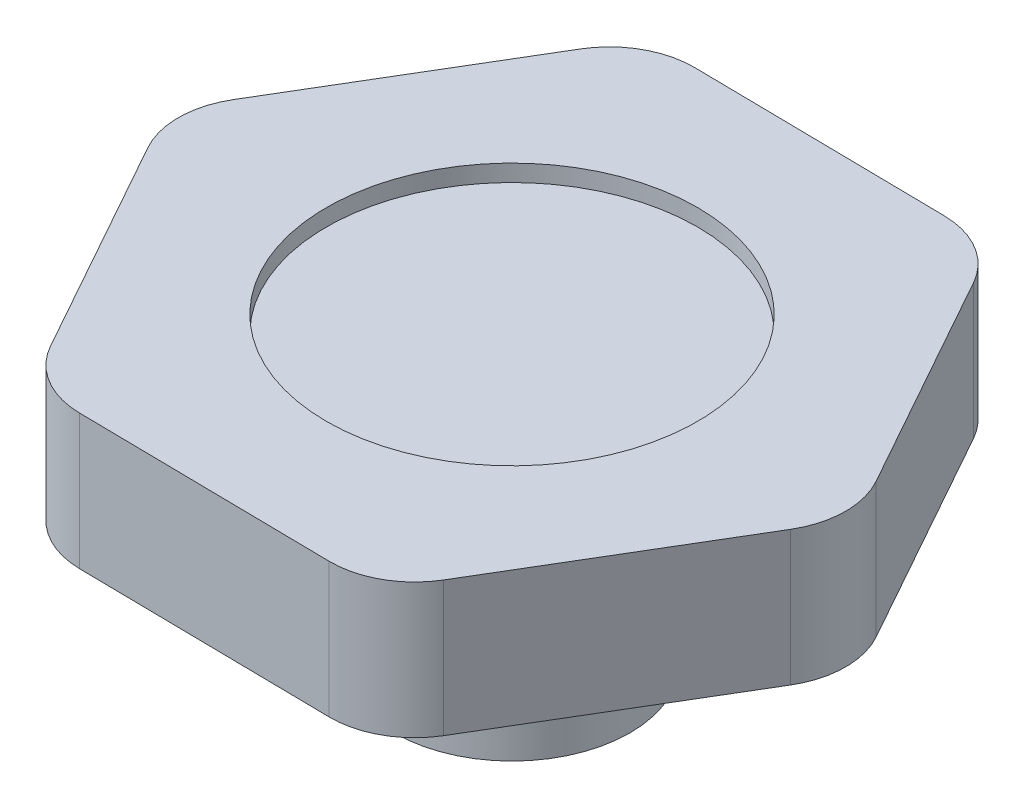
SolidWorks part; units mm, degrees
ref_plane "Front Plane" through (0, 0, 0) normal (0, 0, 1) x (1, 0, 0)
ref_plane "Top Plane" through (0, 0, 0) normal (0, 1, 0) x (1, 0, 0)
ref_plane "Right Plane" through (0, 0, 0) normal (1, 0, 0) x (0, 0, -1)
sketch "Sketch1" plane through (0, 0, 0) normal (0, 1, 0) x (1, 0, 0)
  circle A1 centre (0, 0) radius 7
  dimension "D1" = 14
extrude "Boss-Extrude1" add sketch "Sketch1" along normal blind 10
sketch "Sketch2" plane through (0, 0, 0) normal (0, -1, 0) x (1, 0, 0)
  line L1 (4.7639, -2.7182) -> (4.736, 2.7665)
  line L2 (4.736, 2.7665) -> (-0.0279, 5.4848)
  line L3 (-0.0279, 5.4848) -> (-4.7639, 2.7182)
  line L4 (-4.7639, 2.7182) -> (-4.736, -2.7665)
  line L5 (-4.736, -2.7665) -> (0.0279, -5.4848)
  line L6 (0.0279, -5.4848) -> (4.7639, -2.7182)
  circle A0 centre (0, 0) radius 4.75 construction
extrude "Cut-Extrude1" cut sketch "Sketch2" against normal blind 5
sketch "Sketch3" plane through (0, 10, 0) normal (0, 1, 0) x (1, 0, 0)
  line L1 (20.7825, -0.295) -> (10.6467, 17.8507)
  line L2 (10.6467, 17.8507) -> (-10.1358, 18.1457)
  line L3 (-10.1358, 18.1457) -> (-20.7825, 0.295)
  line L4 (-20.7825, 0.295) -> (-10.6467, -17.8507)
  line L5 (-10.6467, -17.8507) -> (10.1358, -18.1457)
  line L6 (10.1358, -18.1457) -> (20.7825, -0.295)
  circle A0 centre (0, 0) radius 18 construction
extrude "Boss-Extrude2" add sketch "Sketch3" along normal blind 8
fillet "Fillet1" radius 5 6 edges at (-10.6467, 14, 17.8507) (-20.7825, 14, -0.295) (-10.1358, 14, -18.1457) (10.6467, 14, -17.8507) (20.7825, 14, 0.295) (10.1358, 14, 18.1457)
sketch "Sketch4" plane through (0, 18, 0) normal (0, 1, 0) x (1, 0, 0)
  circle A0 centre (0, 0) radius 11
extrude "Cut-Extrude2" cut sketch "Sketch4" against normal blind 1
